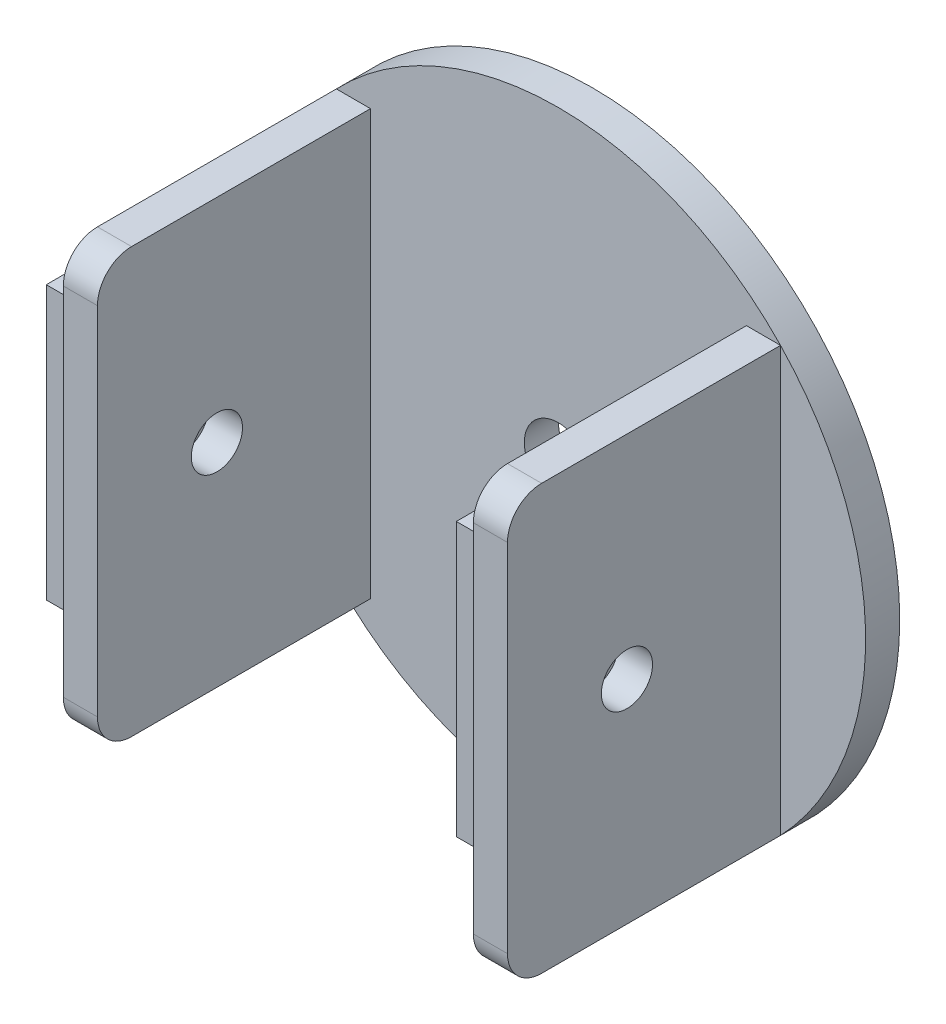
SolidWorks part; units mm, degrees
ref_plane "Front Plane" through (0, 0, 0) normal (0, 0, 1) x (1, 0, 0)
ref_plane "Top Plane" through (0, 0, 0) normal (0, 1, 0) x (1, 0, 0)
ref_plane "Right Plane" through (0, 0, 0) normal (1, 0, 0) x (0, 0, -1)
sketch "Sketch1" plane through (0, 0, 0) normal (0, 0, 1) x (1, 0, 0)
  circle A0 centre (0, 0) radius 90
  dimension "D1" = 180
extrude "Boss-Extrude1" add sketch "Sketch1" along normal blind 10
sketch "Sketch2" plane through (0, 0, 10) normal (0, 0, 1) x (1, 0, 0)
  line L0 (0, 90) -> (0, -90) construction
  line L1 (-65.071, 62.1753) -> (-65.071, -62.1753)
  line L2 (-55.071, 62.1753) -> (-55.071, -62.1753)
  line L3 (-65.071, -62.1753) -> (-55.071, -62.1753)
  line L4 (-65.071, 62.1753) -> (-55.071, 62.1753)
  line L5 (65.071, 62.1753) -> (55.071, 62.1753)
  line L6 (65.071, -62.1753) -> (55.071, -62.1753)
  line L7 (55.071, 62.1753) -> (55.071, -62.1753)
  line L8 (65.071, 62.1753) -> (65.071, -62.1753)
  circle A0 centre (0, 0) radius 90 construction
  dimension "D1" = 10
extrude "Boss-Extrude2" add sketch "Sketch2" along normal blind 80
fillet "Fillet1" radius 10 4 edges at (60.071, 62.1753, 90) (60.071, -62.1753, 90) (-60.071, 62.1753, 90) (-60.071, -62.1753, 90)
sketch "Sketch3" plane through (-65.071, 0, 0) normal (-1, 0, 0) x (0, 0, 1)
  line L0 (0, 0) -> (114.1464, 0) construction
  line L1 (0, 90) -> (0, -90) construction
  line L2 (90, 52.1753) -> (90, -52.1753) construction
  circle A0 centre (55, 0) radius 7.5
  dimension "D2" = 15
  dimension "D1" = 35
extrude "Cut-Extrude1" cut sketch "Sketch3" against normal through all
sketch "Sketch4" plane through (0, 0, 10) normal (0, 0, 1) x (1, 0, 0)
  circle A0 centre (0, 0) radius 10
  dimension "D1" = 20
extrude "Cut-Extrude2" cut sketch "Sketch4" against normal blind 30 contours A0
sketch "Sketch7" plane through (-65.071, 0, 0) normal (-1, 0, 0) x (0, 0, 1)
  line L2 (30, 40) -> (30, -40)
  line L4 (80, 40) -> (80, -40)
  line L5 (30, -40) -> (42.9549, -40)
  line L6 (42.9549, -40) -> (42.9549, -41.5)
  line L11 (30, 40) -> (42.9549, 40)
  line L12 (42.9549, 40) -> (42.9549, 41.5)
  line L13 (42.9549, 41.5) -> (67.0451, 41.5)
  line L14 (67.0451, 41.5) -> (67.0451, 40)
  line L15 (67.0451, 40) -> (80, 40)
  line L16 (42.9549, -41.5) -> (67.0451, -41.5)
  line L17 (67.0451, -41.5) -> (67.0451, -40)
  line L18 (67.0451, -40) -> (80, -40)
  line L19 (80, 0) -> (30, 0) construction
  line L20 (55, 41.5) -> (55, -41.5) construction
  point P0 (55, 0)
extrude "Boss-Extrude5" add sketch "Sketch7" along normal blind 15
sketch "Sketch8" plane through (55.071, 0, 0) normal (-1, 0, 0) x (0, 0, 1)
  line L0 (47.5, 0) -> (62.5, 0) construction
  line L1 (30, 40) -> (30, -40)
  line L2 (80, 40) -> (80, -40)
  line L3 (30, -40) -> (42.9549, -40)
  line L4 (42.9549, -40) -> (42.9549, -41.5)
  line L5 (30, 40) -> (43.6553, 40)
  line L6 (43.6553, 40) -> (43.6553, 41.5)
  line L7 (43.6553, 41.5) -> (66.3447, 41.5)
  line L8 (66.3447, 41.5) -> (66.3447, 40)
  line L9 (66.3447, 40) -> (80, 40)
  line L10 (42.9549, -41.5) -> (67.0451, -41.5)
  line L11 (67.0451, -41.5) -> (67.0451, -40)
  line L12 (67.0451, -40) -> (80, -40)
  line L13 (80, 0) -> (30, 0) construction
  line L14 (55, 41.5) -> (55, -41.5) construction
  line L15 (55, 7.5) -> (55, -7.5) construction
  circle A0 centre (55, 0) radius 7.5 construction
  point P6 (55.7005, -1.889)
  dimension "D1" = 0
extrude "Boss-Extrude6" add sketch "Sketch8" along normal blind 15
